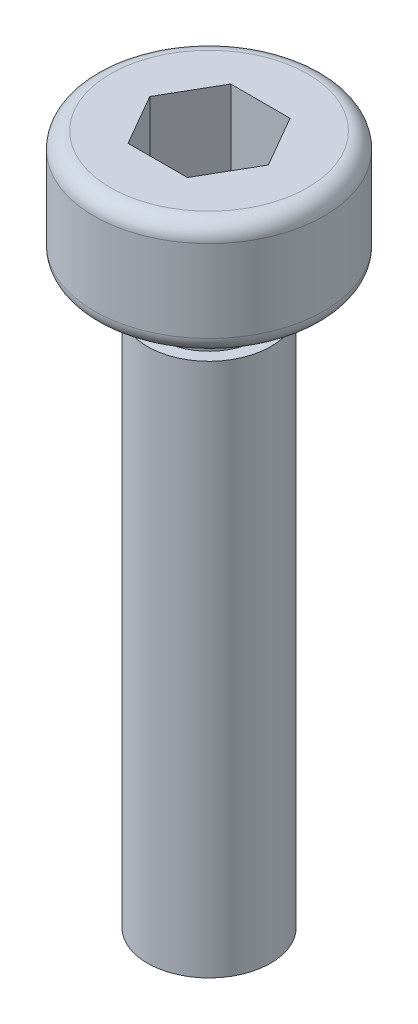
SolidWorks part; units mm, degrees
material "AISI 304"
ref_plane "前视基准面" through (0, 0, 0) normal (0, 0, 1) x (1, 0, 0)
ref_plane "上视基准面" through (0, 0, 0) normal (0, 1, 0) x (1, 0, 0)
ref_plane "右视基准面" through (0, 0, 0) normal (1, 0, 0) x (0, 0, -1)
sketch "草图1" plane through (0, 0, 0) normal (0, 0, 1) x (1, 0, 0)
  line L0 (0, 0) -> (0, 16.8) construction
  line L1 (0, 16.8) -> (-2.4, 16.8)
  line L2 (-2.8, 16.4) -> (-2.8, 14.4)
  line L3 (-2.4, 14) -> (-1.2, 14)
  line L4 (-1.2, 14) -> (-1.2, 13)
  line L5 (-1.2, 13) -> (-1.5, 13)
  line L6 (-1.5, 13) -> (-1.5, 0)
  line L7 (-1.5, 0) -> (0, 0)
  line L8 (0, 0) -> (0, 16.8)
  arc A0 (-2.8, 14.4) -> (-2.4, 14) centre (-2.4, 14.4) ccw
  arc A1 (-2.4, 16.8) -> (-2.8, 16.4) centre (-2.4, 16.4) ccw
  point P11 (-2.8, 14)
  point P14 (-2.8, 16.8)
  dimension "D7" = 0.4
  dimension "D1" = 14
  dimension "D2" = 2.8
  dimension "D3" = 5.6
  dimension "D4" = 3
  dimension "D5" = 1
  dimension "D6" = 1.2
revolve "旋转1" add sketch "草图1" angle 360 about L0
cosmetic thread "装饰螺纹线1" parameters "D2"=2.439
sketch "草图2" plane through (0, 16.8, 0) normal (0, 1, 0) x (1, 0, 0)
  line L1 (-0.7217, 1.25) -> (-1.4434, 0)
  line L2 (-1.4434, 0) -> (-0.7217, -1.25)
  line L3 (-0.7217, -1.25) -> (0.7217, -1.25)
  line L4 (0.7217, -1.25) -> (1.4434, 0)
  line L5 (1.4434, 0) -> (0.7217, 1.25)
  line L6 (0.7217, 1.25) -> (-0.7217, 1.25)
  circle A0 centre (0, 0) radius 1.25 construction
  dimension "D1" = 2.5
extrude "切除-拉伸1" cut sketch "草图2" against normal blind 2
